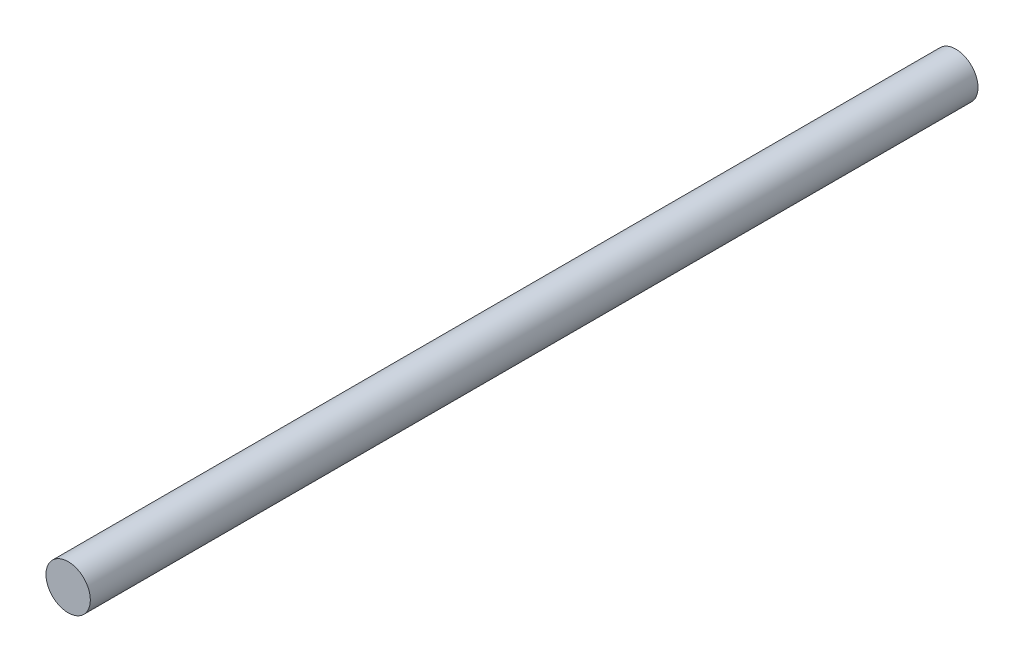
SolidWorks part; units mm, degrees
ref_plane "Спереди" through (0, 0, 0) normal (0, 0, 1) x (1, 0, 0)
ref_plane "Сверху" through (0, 0, 0) normal (0, 1, 0) x (1, 0, 0)
ref_plane "Справа" through (0, 0, 0) normal (1, 0, 0) x (0, 0, -1)
sketch "Эскиз1" plane through (0, 0, 0) normal (0, 0, 1) x (1, 0, 0)
  circle A0 centre (0, 0) radius 2
  dimension "D1" = 4
extrude "Шпилька на тяги" add sketch "Эскиз1" along normal blind 80
